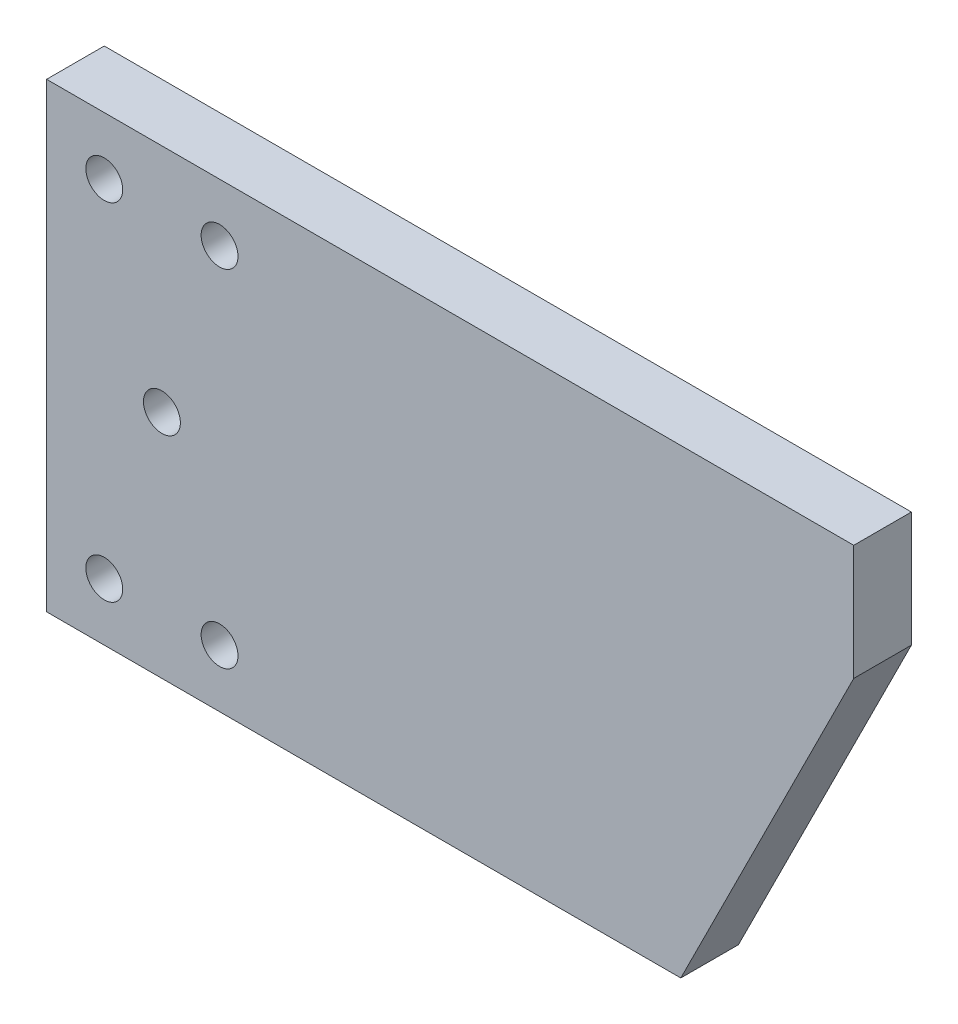
SolidWorks part; units mm, degrees
ref_plane "Front Plane" through (0, 0, 0) normal (0, 0, 1) x (1, 0, 0)
ref_plane "Top Plane" through (0, 0, 0) normal (0, 1, 0) x (1, 0, 0)
ref_plane "Right Plane" through (0, 0, 0) normal (1, 0, 0) x (0, 0, -1)
sketch "Sketch1" plane through (0, 0, 0) normal (0, 0, 1) x (1, 0, 0)
  line L0 (69.85, 0) -> (88.9, 38.1)
  line L1 (0, 0) -> (69.85, 0)
  line L2 (0, 0) -> (0, 50.8)
  line L3 (0, 50.8) -> (88.9, 50.8)
  line L4 (88.9, 38.1) -> (88.9, 50.8)
  circle A0 centre (6.35, 6.35) radius 2.032
  circle A1 centre (19.05, 6.35) radius 2.032
  circle A2 centre (19.05, 44.45) radius 2.032
  circle A3 centre (6.35, 44.45) radius 2.032
  circle A4 centre (12.7, 25.4) radius 2.032
  dimension "D5" = 6.35
  dimension "D7" = 4.064
  dimension "D10" = 25.4
  dimension "D1" = 50.8
  dimension "D2" = 69.85
  dimension "D3" = 88.9
  dimension "D4" = 12.7
  dimension "D6" = 6.35
  dimension "D11" = 12.7
  dimension "D8" = 2
  dimension "D9" = 2
extrude "Boss-Extrude1" add sketch "Sketch1" along normal blind 6.35
